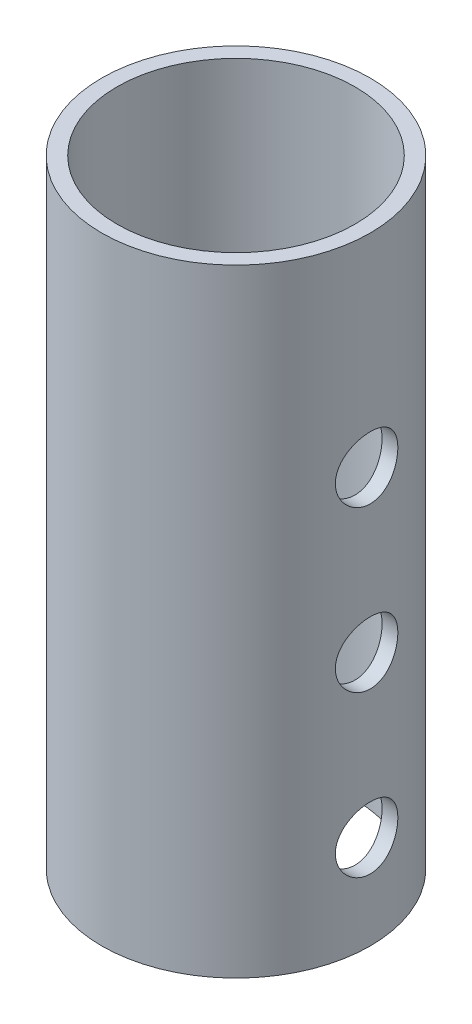
SolidWorks part; units mm, degrees
material "PTFE (general)"
ref_plane "Front Plane" through (0, 0, 0) normal (0, 0, 1) x (1, 0, 0)
ref_plane "Top Plane" through (0, 0, 0) normal (0, 1, 0) x (1, 0, 0)
ref_plane "Right Plane" through (0, 0, 0) normal (1, 0, 0) x (0, 0, -1)
sketch "Sketch1" plane through (0, 0, 0) normal (0, 1, 0) x (1, 0, 0)
  circle A0 centre (0, 0) radius 42.725
  circle A1 centre (0, 0) radius 37.875
  dimension "D1" = 85.45
  dimension "D2" = 75.75
extrude "Boss-Extrude1" add sketch "Sketch1" along normal blind 196.5
sketch "Sketch2" plane through (0, 0, 0) normal (1, 0, 0) x (0, 0, -1)
  line L0 (37.875, 196.5) -> (-37.875, 196.5) construction
  circle A0 centre (0, 131.8) radius 9.94
  circle A1 centre (0, 80.8) radius 9.94
  circle A2 centre (0, 29.8) radius 9.94
  dimension "D2" = 19.88
  dimension "D3" = 19.88
  dimension "D4" = 19.88
  dimension "D1" = 64.7
  dimension "D5" = 51
  dimension "D6" = 51
extrude "Cut-Extrude1" cut sketch "Sketch2" along normal through all
sketch "Sketch4" plane through (0, 0, 0) normal (1, 0, 0) x (0, 0, -1)
  circle A0 centre (0, 106.3) radius 7.5
  circle A4 centre (0, 80.8) radius 9.94 construction
  dimension "D1" = 15
  dimension "D3" = 25.5
extrude "Cut-Extrude2" cut sketch "Sketch4" against normal through all
